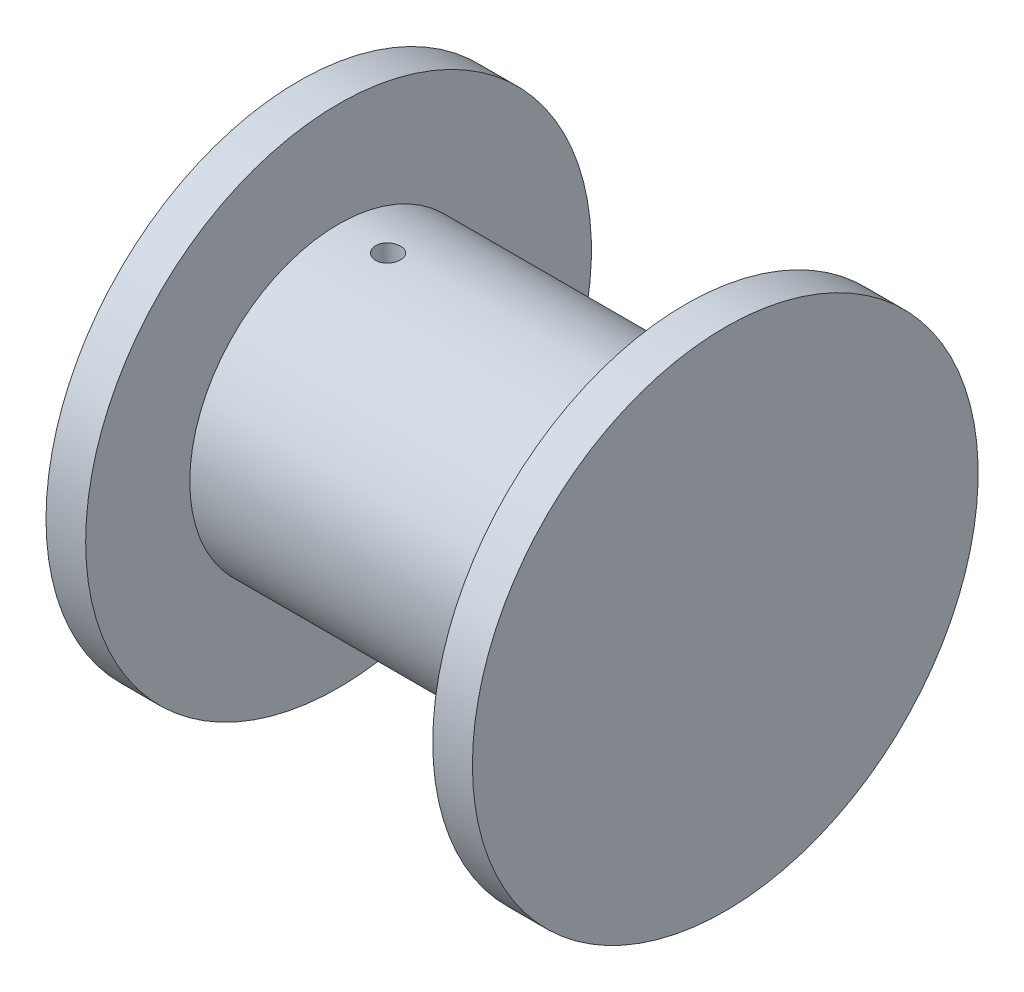
SolidWorks part; units mm, degrees
material "6061 Alloy"
ref_plane "Front Plane" through (0, 0, 0) normal (0, 0, 1) x (1, 0, 0)
ref_plane "Top Plane" through (0, 0, 0) normal (0, 1, 0) x (1, 0, 0)
ref_plane "Right Plane" through (0, 0, 0) normal (1, 0, 0) x (0, 0, -1)
sketch "Sketch1" plane through (0, 0, 0) normal (0, 0, 1) x (1, 0, 0)
  line L0 (0, 0) -> (0, 3)
  line L1 (0, 3) -> (0, 25.5)
  line L2 (0, 25.5) -> (4, 25.5)
  line L3 (4, 25.5) -> (4, 15)
  line L4 (4, 15) -> (39, 15)
  line L5 (39, 15) -> (39, 25.5)
  line L6 (39, 25.5) -> (43, 25.5)
  line L7 (43, 25.5) -> (43, 3)
  line L8 (43, 3) -> (43, 0)
  line L9 (0, 0) -> (43, 0) construction
  line L10 (0, 0) -> (43, 0)
  dimension "D1" = 10.5
  dimension "D2" = 10.5
  dimension "D3" = 43
  dimension "D4" = 3
  dimension "D5" = 3
  dimension "D6" = 12
  dimension "D7" = 4
  dimension "D8" = 4
  dimension "D9" = 35
revolve "Revolve1" add sketch "Sketch1" angle 360 about L10
hole_wizard "M3 Tapped Hole1" positions "Sketch6" profile "Sketch7" tap size "M3" standard "ISO"
sketch "Sketch6" plane through (0, 0, 0) normal (0, 1, 0) x (1, 0, 0)
  point P0 (9, 0)
  dimension "D1" = 9
sketch "Sketch7" plane through (9, 0, 0) normal (1, 0, 0) x (0, 0, -1)
  line L0 (0, 0) -> (0, 15)
  line L1 (0, 15) -> (1.25, 15)
  line L2 (1.25, 15) -> (1.25, 0)
  line L5 (1.25, 0) -> (0, 0)
  line L11 (0, -6.35) -> (0, 107.95) construction
  dimension "Thru Tap Drill Dia." = 2.5
  dimension "Thru Tap Drill Depth" = 15
cosmetic thread "Hole Thread1" parameters "D2"=3
sketch "Sketch8" plane through (0, 0, 0) normal (-1, 0, 0) x (0, 0, 1)
  line L3 (-1.6583, 2.5) -> (1.6583, 2.5)
  arc A0 (-1.6583, 2.5) -> (1.6583, 2.5) centre (0, 0) ccw
  point P7 (0, 2.5)
  dimension "D1" = 6
  dimension "D2" = 2.5
extrude "Cut-Extrude1" cut sketch "Sketch8" against normal blind 12
